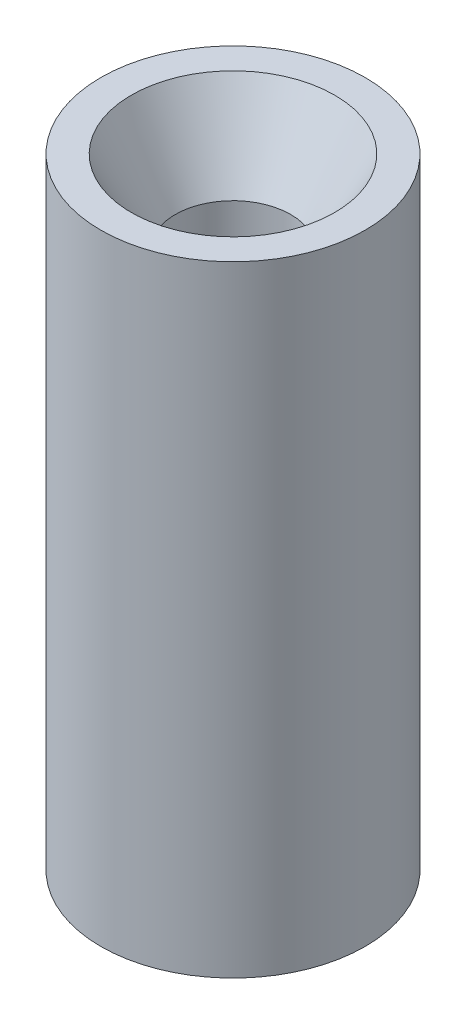
SolidWorks part; units mm, degrees
ref_plane "Alzado" through (0, 0, 0) normal (0, 0, 1) x (1, 0, 0)
ref_plane "Planta" through (0, 0, 0) normal (0, 1, 0) x (1, 0, 0)
ref_plane "Vista lateral" through (0, 0, 0) normal (1, 0, 0) x (0, 0, -1)
sketch "Croquis2" plane through (0, 0, 0) normal (0, 0, 1) x (1, 0, 0)
  line L0 (0, -23.5849) -> (0, 38.9524) construction
  line L2 (-10, 0) -> (-5.675, 8)
  line L3 (-5.675, 8) -> (-5.675, 53)
  line L4 (-5.675, 53) -> (-10, 61)
  line L5 (-10, 61) -> (-13, 61)
  line L6 (-13, 61) -> (-13, 0)
  line L7 (-13, 0) -> (-10, 0)
  point P7 (0, 0)
  dimension "D1" = 8
  dimension "D2" = 3
  dimension "D3" = 11.35
  dimension "D4" = 61
  dimension "D5" = 26
  dimension "D6" = 4.325
revolve "Revolución1" add sketch "Croquis2" angle 360 about L0
